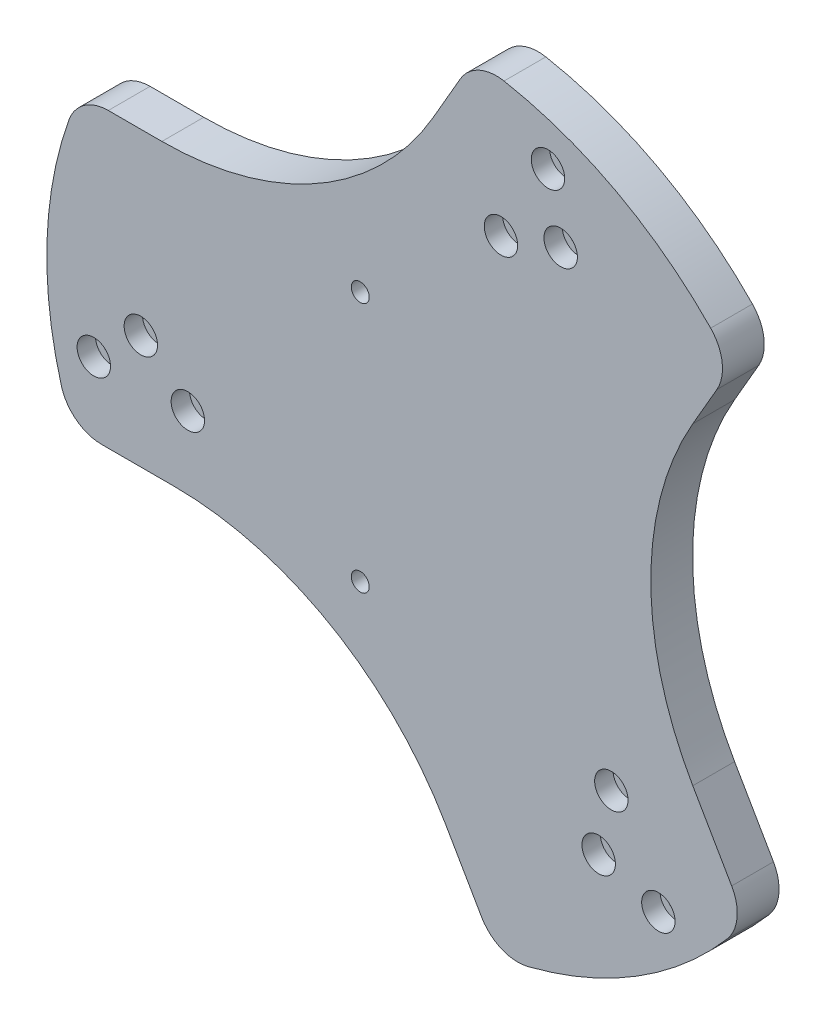
SolidWorks part; units mm, degrees
ref_plane "Ebene vorne" through (0, 0, 0) normal (0, 0, 1) x (1, 0, 0)
ref_plane "Ebene oben" through (0, 0, 0) normal (0, 1, 0) x (1, 0, 0)
ref_plane "Ebene rechts" through (0, 0, 0) normal (1, 0, 0) x (0, 0, -1)
sketch "Skizze1" plane through (0, 0, 0) normal (0, 0, 1) x (1, 0, 0)
  circle A0 centre (0, 0) radius 92.5
  dimension "D1" = 185
extrude "Aufsatz-Linear austragen1" add sketch "Skizze1" along normal blind 10
sketch "Skizze4" plane through (0, 0, 10) normal (0, 0, 1) x (1, 0, 0)
  circle A0 centre (-81.25, -15.25) radius 4.2332
  circle A1 centre (-58.75, -15.25) radius 5.6443
  circle A2 centre (16.1681, 58.504) radius 5.6443
  circle A3 centre (27.4181, 77.9896) radius 4.2332
  circle A4 centre (42.5819, -43.254) radius 5.6443
  circle A5 centre (53.8319, -62.7396) radius 4.2332
  circle A6 centre (39.5466, -57.9968) radius 1.2362
  circle A7 centre (-70, -5.25) radius 1.2362
  circle A8 centre (30.4534, 63.2468) radius 1.2362
  point P15 (0, 0)
  point P23 (0, 0)
  dimension "D1" = 22.5
  dimension "D2" = 58.75
  dimension "D4" = 15.25
  dimension "D3" = 3
  dimension "D5" = 3
hole_wizard "Stirnsenkung für M4 Zylinderschraube mit Innensechskant1" positions "3D-Skizze2" profile "Skizze5" counterbore size "M4" standard "DIN" end condition through all
sketch3d "3D-Skizze2"
  point P0 (-81.25, -15.25, 10)
  point P3 (-58.75, -15.25, 10)
  point P6 (16.1681, 58.504, 10)
  point P9 (27.4181, 77.9896, 10)
  point P12 (42.5819, -43.254, 10)
  point P15 (53.8319, -62.7396, 10)
  point P18 (39.5466, -57.9968, 10)
  point P21 (30.4534, 63.2468, 10)
  point P24 (-70, -5.25, 10)
sketch "Skizze5" plane through (-81.25, -15.25, 10) normal (1, 0, 0) x (0, -1, 0)
  line L0 (0, 0) -> (0, 10)
  line L1 (0, 10) -> (2.25, 10)
  line L3 (2.25, 10) -> (2.25, 4.4)
  line L4 (2.25, 4.4) -> (4, 4.4)
  line L5 (4, 4.4) -> (4, 0)
  line L7 (4, 0) -> (0, 0)
  line L11 (0, -6.35) -> (0, 107.95) construction
  dimension "Bohrerdurchmesser" = 4.5
  dimension "Bohrungstiefe" = 10
  dimension "Senkdurchmesser2" = 8
  dimension "Senktiefe2" = 4.4
sketch "Skizze6" plane through (0, 0, 0) normal (0, 0, -1) x (-1, 0, 0)
  circle A0 centre (-53.8074, 64.1971) radius 0.5947
  circle A1 centre (-37.3529, 73.6971) radius 0.7301
sketch "Skizze10" plane through (0, 0, 0) normal (0, 0, -1) x (-1, 0, 0)
  line L0 (86.6025, -32.5) -> (18.7639, -32.5)
  line L1 (84.5577, 37.5) -> (21.6506, 37.5)
  line L2 (-74.7548, -54.4791) -> (-40.4145, 5)
  line L3 (-15.1554, -91.25) -> (18.7639, -32.5)
  line L4 (-9.8029, 91.9791) -> (21.6506, 37.5)
  line L5 (-71.4471, 58.75) -> (-40.4145, 5)
  line L6 (-57.5847, -24.7395) -> (3.0371, -59.7395) construction
  line L7 (85.7839, -32.5) -> (85.7839, 37.5) construction
  line L8 (-55.9308, 31.875) -> (4.691, 66.875) construction
  arc A0 (86.6025, -32.5) -> (84.5577, 37.5) centre (0, 0) ccw
  arc A1 (-74.7548, -54.4791) -> (-15.1554, -91.25) centre (0, 0) ccw
  arc A2 (-9.8029, 91.9791) -> (-71.4471, 58.75) centre (0, 0) ccw
  circle A3 centre (0, 0) radius 92.5 construction
  point P16 (0, 0)
  dimension "D1" = 70
  dimension "D2" = 37.5
  dimension "D3" = 120
  dimension "D4" = 120
  dimension "D5" = 37.5
  dimension "D6" = 37.5
extrude "Schnitt-Linear austragen1" cut sketch "Skizze10" against normal through all flip side to cut
fillet "Verrundung2" radius 10 6 edges at (-86.6025, -32.5, 5) (-84.5577, 37.5, 5) (15.1554, -91.25, 5) (74.7548, -54.4791, 5) (71.4471, 58.75, 5) (9.8029, 91.9791, 5)
sketch "Skizze11" plane through (0, 0, 10) normal (0, 0, 1) x (1, 0, 0)
  circle A0 centre (105, -82.5) radius 3.1761
  circle A1 centre (105, -37.5) radius 3.7043
  circle A2 centre (105, 37.5) radius 2.7921
  circle A3 centre (105, 82.5) radius 2.9027
  circle A4 centre (-70, -19.5585) radius 2.9557
  circle A5 centre (-70, 25.4415) radius 2.4408
  arc A7 (22.6493, -89.6842) -> (70.3074, -60.1093) centre (0, 0) ccw construction
  circle A8 centre (-81.25, -15.25) radius 2.25 construction
  arc A9 (-87.2098, 30.8333) -> (-88.9935, -25.2273) centre (0, 0) ccw construction
  point P17 (-92.4532, 2.9415)
  dimension "D1" = 45
  dimension "D2" = 45
  dimension "D3" = 45
  dimension "D5" = 37.5
  dimension "D6" = 11.25
  dimension "D7" = 22.5
  dimension "D4" = 75
  dimension "D8" = 175
sketch "Skizze13" plane through (0, 0, 10) normal (0, 0, 1) x (1, 0, 0)
  circle A0 centre (32.6184, 61.9968) radius 3.2264
  circle A1 centre (-70, -5.25) radius 3.2264
  circle A2 centre (39.5466, -60.4968) radius 3.2264
  circle A4 centre (-81.25, -15.25) radius 2.25 construction
  circle A5 centre (-81.25, -15.25) radius 4 construction
  point P15 (0.7217, -1.25)
  dimension "D2" = 10
  dimension "D3" = 11.25
  dimension "D1" = 3
fillet "Verrundung3" radius 75 3 edges at (-18.7639, -32.5, 5) (40.4145, 5, 5) (-21.6506, 37.5, 5)
sketch "Skizze14" plane through (0, 0, 10) normal (0, 0, 1) x (1, 0, 0)
  circle A0 centre (-17.5, 30) radius 2.15
  circle A1 centre (-17.5, -30) radius 2.15
  dimension "D2" = 60
  dimension "D3" = 30
  dimension "D4" = 4.3
  dimension "D1" = 17.5
extrude "Schnitt-Linear austragen2" cut sketch "Skizze14" against normal up to next
sketch "Skizze15" plane through (0, 0, 0) normal (0, 0, -1) x (-1, 0, 0)
  circle A0 centre (17.5, 30) radius 4
  circle A1 centre (17.5, -30) radius 4
  dimension "D1" = 8
extrude "Schnitt-Linear austragen3" cut sketch "Skizze15" against normal blind 4.4
sketch "Skizze18" [suppressed] plane through (0, 0, 0) normal (0, 0, -1) x (-1, 0, 0)
  line L0 (-53.8324, 64.2404) -> (-37.3779, 73.7404)
  line L1 (82.55, 14.5) -> (82.55, -4.5)
  line L2 (-28.7176, -78.7404) -> (-45.1721, -69.2404)
  line L3 (-43.1721, -65.7763) -> (-26.7176, -75.2763)
  line L4 (78.55, 14.5) -> (78.55, -4.5)
  line L5 (-51.8324, 60.7763) -> (-35.3779, 70.2763)
  line L6 (-26.7176, -75.2763) -> (-28.7176, -78.7404)
  line L7 (78.55, 14.5) -> (82.55, 14.5)
  line L8 (-51.8324, 60.7763) -> (-53.8324, 64.2404)
  dimension "D3" = 19
  dimension "D4" = 4
hole_wizard "M3 Gewindebohrung1" positions "Skizze20" profile "Skizze19" tap size "M3" standard "DIN"
sketch "Skizze20" plane through (0, 0, 0) normal (0, 0, -1) x (-1, 0, 0)
  point P0 (82.5, -4.5)
  point P2 (82.5, 14.5)
  point P13 (-45.1471, -69.1971)
  point P14 (-28.6926, -78.6971)
  point P15 (-37.3529, 73.6971)
  point P16 (-53.8074, 64.1971)
  point P17 (0, 0)
  dimension "D1" = 82.5
  dimension "D2" = 19
  dimension "D3" = 4.5
  dimension "D4" = 3
sketch "Skizze19" plane through (-82.5, -4.5, 0) normal (1, 0, 0) x (0, 1, 0)
  line L0 (0, 0) -> (0, 9.2511)
  line L1 (0, 9.2511) -> (1.25, 8.5)
  line L2 (1.25, 8.5) -> (1.25, 0)
  line L5 (1.25, 0) -> (0, 0)
  line L10 (0, 9.2511) -> (-1.25, 8.5) construction
  line L11 (0, -6.35) -> (0, 107.95) construction
  dimension "Bohrerdurchmesser" = 2.5
  dimension "Bohrungstiefe" = 8.5
  dimension "Spitzenwinkel" = 118
cosmetic thread "Bohrungsgewinde1" parameters "D1"=6, "D2"=3
cosmetic thread "Bohrungsgewinde2" parameters "D1"=6, "D2"=3
cosmetic thread "Bohrungsgewinde3" parameters "D1"=6, "D2"=3
cosmetic thread "Bohrungsgewinde4" parameters "D1"=6, "D2"=3
cosmetic thread "Bohrungsgewinde5" parameters "D1"=6, "D2"=3
cosmetic thread "Bohrungsgewinde6" parameters "D1"=6, "D2"=3
cosmetic thread "Bohrungsgewinde7" parameters "D1"=6, "D2"=3
